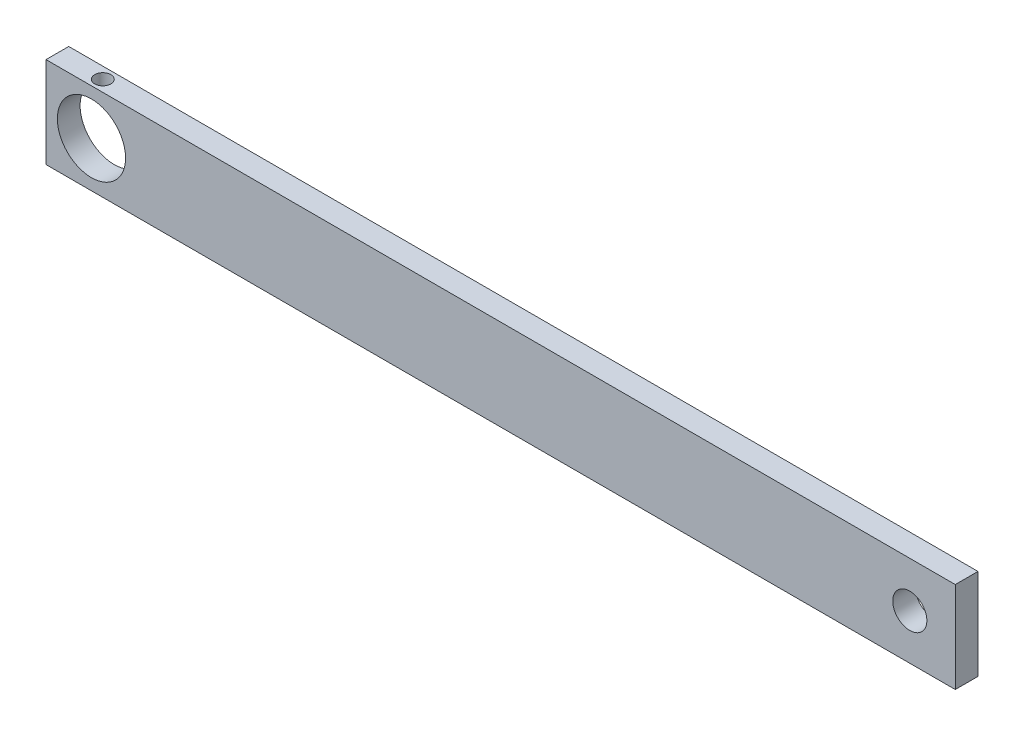
SolidWorks part; units mm, degrees
ref_plane "Front Plane" through (0, 0, 0) normal (0, 0, 1) x (1, 0, 0)
ref_plane "Top Plane" through (0, 0, 0) normal (0, 1, 0) x (1, 0, 0)
ref_plane "Right Plane" through (0, 0, 0) normal (1, 0, 0) x (0, 0, -1)
sketch "Sketch1" plane through (0, 0, 0) normal (0, 0, 1) x (1, 0, 0)
  line L1 (0, 0) -> (127, 0)
  line L2 (0, 0) -> (0, 12.7)
  line L3 (0, 12.7) -> (127, 12.7)
  line L4 (127, 0) -> (127, 12.7)
  circle A2 centre (6.35, 6.35) radius 4.7625
  circle A3 centre (120.65, 6.35) radius 2.3813
  dimension "D9" = 4.7625
  dimension "D10" = 6.35
  dimension "D11" = 6.35
  dimension "D12" = 9.525
  dimension "D13" = 6.35
  dimension "D14" = 6.35
  dimension "D1" = 12.7
  dimension "D2" = 127
other "AlignGroup1"
extrude "Boss-Extrude1" add sketch "Sketch1" along normal blind 3.175
sketch "Sketch2" plane through (0, 12.7, 0) normal (0, 1, 0) x (1, 0, 0)
  line L0 (0, -3.175) -> (0, 0) construction
  line L1 (127, -3.175) -> (0, -3.175) construction
  circle A0 centre (6.35, -1.5875) radius 1.1303
  dimension "D1" = 2.2606
  dimension "D2" = 6.35
  dimension "D3" = 1.5875
extrude "Cut-Extrude1" cut sketch "Sketch2" against normal blind 6.35
